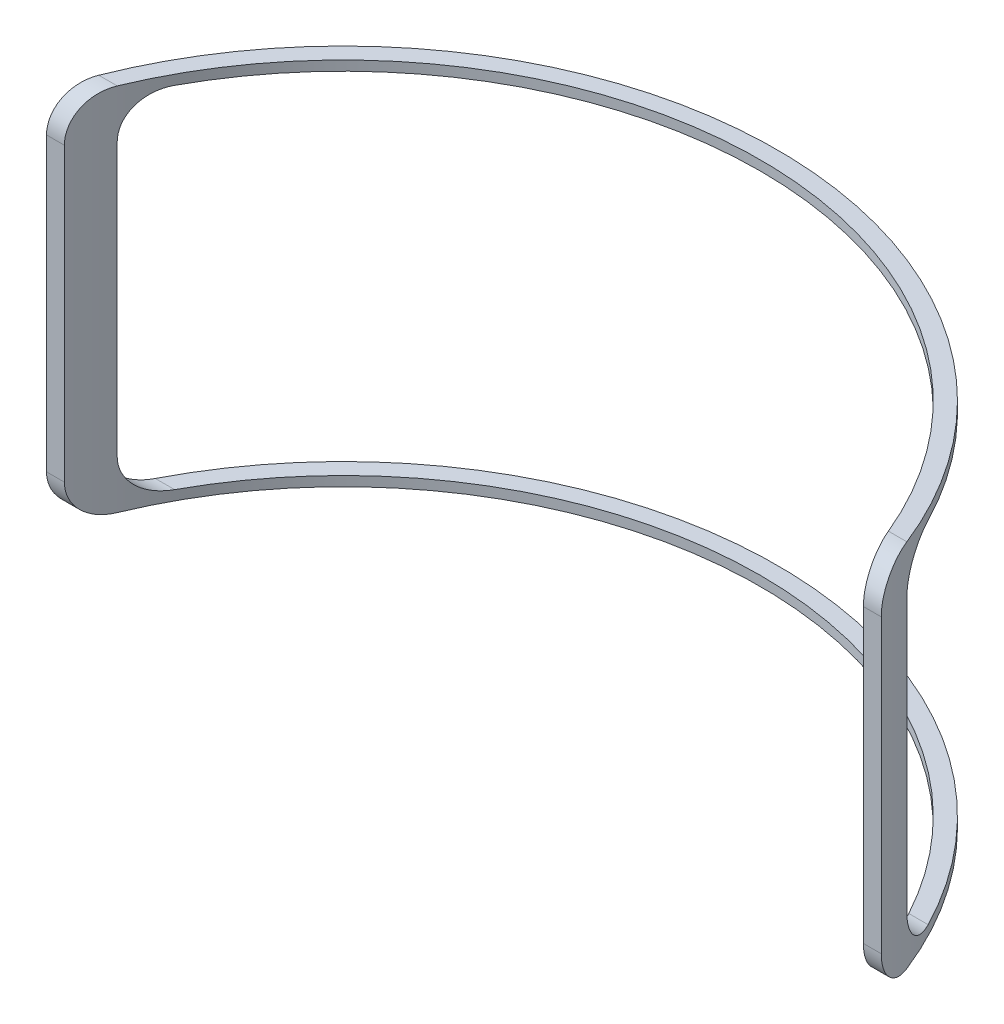
SolidWorks part; units mm, degrees
ref_plane "Front Plane" through (0, 0, 0) normal (0, 0, 1) x (1, 0, 0)
ref_plane "Top Plane" through (0, 0, 0) normal (0, 1, 0) x (1, 0, 0)
ref_plane "Right Plane" through (0, 0, 0) normal (1, 0, 0) x (0, 0, -1)
sketch "Sketch2" plane through (0, 0, 0) normal (0, 1, 0) x (1, 0, 0)
  line L0 (0, 0) -> (10.4809, 0)
  line L1 (2100, 0) -> (2089.5191, 0)
  line L2 (2122.8689, -17) -> (2076.9799, -17)
  line L3 (-22.8689, -17) -> (23.0201, -17)
  arc A0 (0, 0) -> (2100, 0) centre (1050, -327.8719) cw
  arc A1 (10.4809, 0) -> (2089.5191, 0) centre (1050, -327.8719) cw
  arc A2 (-22.8689, -17) -> (2122.8689, -17) centre (1050, -327.8719) cw
  arc A3 (23.0201, -17) -> (2076.9799, -17) centre (1050, -327.8719) cw
  point P6 (0, 0)
  point P8 (0, 0)
  point P10 (0, 0)
  dimension "D2" = 1100
  dimension "D3" = 10
  dimension "D1" = 2100
  dimension "D4" = 17
extrude "Boss-Extrude2" add sketch "Sketch2" along normal blind 950 contours A2 L2 A3 L3
fillet "Fillet2" radius 100 4 edges at (2099.9244, 0, 17) (2099.9244, 950, 17) (0.0756, 0, 17) (0.0756, 950, 17)
ref_plane "Plane2" through (0, 25, 0) normal (0, -1, 0) x (-1, 0, 0)
sketch "Sketch4" plane through (0, 25, 0) normal (0, -1, 0) x (-1, 0, 0)
  line L6 (-2088.6882, 83) -> (-2041.2181, 83)
  line L7 (-58.7819, 83) -> (-11.3118, 83)
  line L8 (-2088.6882, 83) -> (-2041.2181, 83)
  line L9 (-58.7819, 83) -> (-11.3118, 83)
  arc A8 (-11.3118, 83) -> (-2088.6882, 83) centre (-1050, -327.8719) ccw
  arc A9 (-58.7819, 83) -> (-2041.2181, 83) centre (-1050, -327.8719) ccw
  arc A10 (-11.3118, 83) -> (-2088.6882, 83) centre (-1050, -327.8719) ccw
  arc A11 (-58.7819, 83) -> (-2041.2181, 83) centre (-1050, -327.8719) ccw
  dimension "D1" = 0
extrude "Cut-Extrude3" cut sketch "Sketch4" against normal blind 900
fillet "Fillet3" radius 100 4 edges at (35.0468, 25, -83) (2064.9532, 25, -83) (2064.9532, 925, -83) (35.0468, 925, -83)
